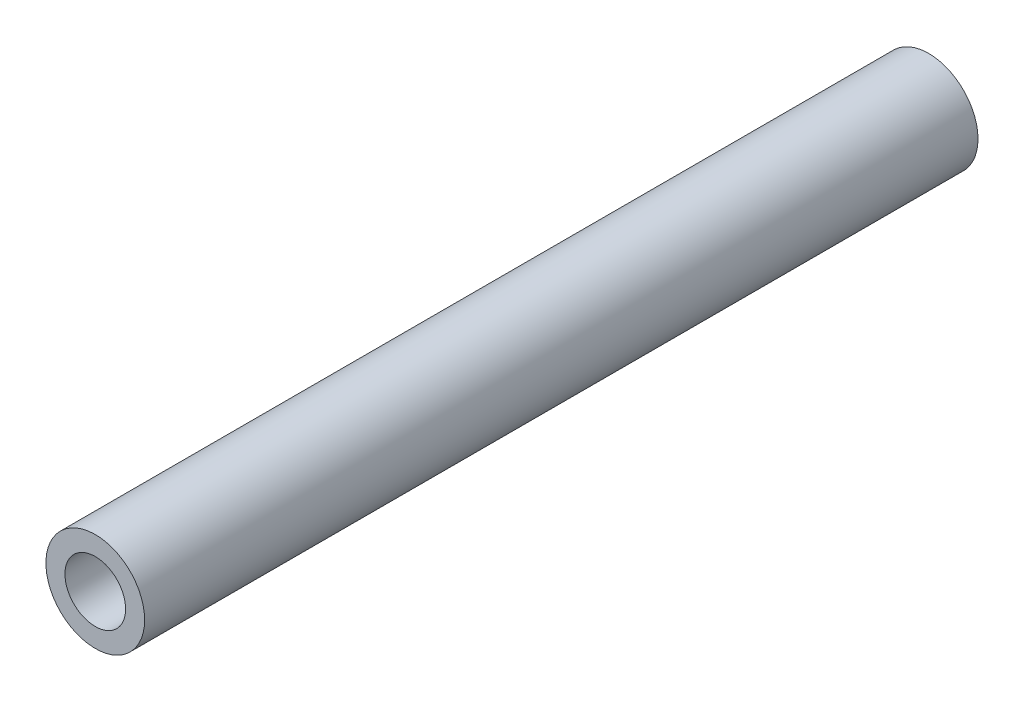
SolidWorks part; units mm, degrees
ref_plane "Front Plane" through (0, 0, 0) normal (0, 0, 1) x (1, 0, 0)
ref_plane "Top Plane" through (0, 0, 0) normal (0, 1, 0) x (1, 0, 0)
ref_plane "Right Plane" through (0, 0, 0) normal (1, 0, 0) x (0, 0, -1)
sketch "Sketch1" plane through (0, 0, 0) normal (0, 0, 1) x (1, 0, 0)
  circle A0 centre (0, 0) radius 3.9688
  circle A1 centre (0, 0) radius 2.4384
  dimension "OD" = 7.9375
  dimension "ID" = 4.8768
extrude "Extrude1" add sketch "Sketch1" along normal mid plane 67.0052
sketch "Sketch2" plane through (0, 0, 0) normal (1, 0, 0) x (0, 0, -1)
  line L0 (-33.5026, -2.4384) -> (33.5026, -2.4384) construction
  line L3 (33.5026, 2.4384) -> (-33.5026, 2.4384) construction
  line L5 (-33.5026, -2.4384) -> (33.5026, -2.4384)
  line L6 (33.5026, 2.4384) -> (-33.5026, 2.4384)
sketch "Sketch4" plane through (0, 0, 33.5026) normal (0, 0, 1) x (1, 0, 0)
  line L0 (0, 0) -> (-1.7242, 1.7242)
  line L1 (0, -55) -> (0, 55) construction
  circle A0 centre (0, 0) radius 2.4384 construction
  dimension "D1" = 45
